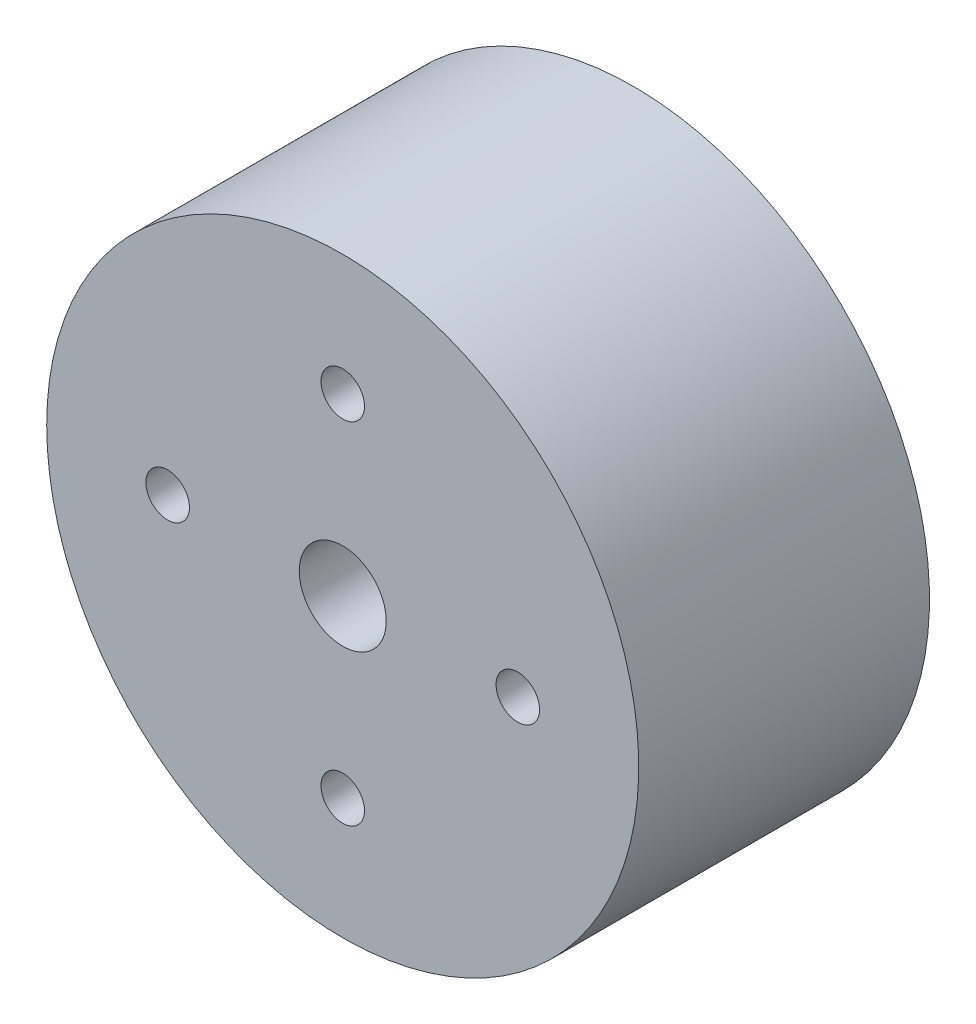
SolidWorks part; units mm, degrees
ref_plane "前视基准面" through (0, 0, 0) normal (0, 0, 1) x (1, 0, 0)
ref_plane "上视基准面" through (0, 0, 0) normal (0, 1, 0) x (1, 0, 0)
ref_plane "右视基准面" through (0, 0, 0) normal (1, 0, 0) x (0, 0, -1)
sketch "草图1" plane through (0, 0, 0) normal (0, 0, 1) x (1, 0, 0)
  circle A0 centre (0, 0) radius 13.95
  circle A1 centre (0, 0) radius 2.05
  dimension "D1" = 4.1
  dimension "D2" = 27.9
extrude "凸台-拉伸1" add sketch "草图1" along normal blind 13.7
sketch "草图2" plane through (0, 0, 0) normal (0, 0, 1) x (1, 0, 0)
  circle A0 centre (0, 0) radius 8.25 construction
  point P3 (0, 8.25)
  point P4 (8.25, 0)
  point P5 (0, -8.25)
  point P6 (-8.25, 0)
  dimension "D1" = 16.5
hole_wizard "M2.5 螺纹孔1" positions "草图3" profile "草图4" tap size "M2.5" standard "GB" end condition through all
sketch "草图3" plane through (0, 0, 13.7) normal (0, 0, 1) x (1, 0, 0)
  point P0 (0, 8.25)
  point P3 (8.25, 0)
  point P6 (0, -8.25)
  point P9 (-8.25, 0)
sketch "草图4" plane through (0, 8.25, 13.7) normal (1, 0, 0) x (0, -1, 0)
  line L0 (0, 0) -> (0, 13.7)
  line L1 (0, 13.7) -> (1.025, 13.7)
  line L2 (1.025, 13.7) -> (1.025, 0)
  line L5 (1.025, 0) -> (0, 0)
  line L11 (0, -6.35) -> (0, 107.95) construction
  dimension "通孔螺纹孔钻头直径" = 2.05
  dimension "通孔螺纹孔钻头深度" = 13.7
cosmetic thread "孔螺蚊线1"
cosmetic thread "孔螺蚊线2"
cosmetic thread "孔螺蚊线3"
cosmetic thread "孔螺蚊线4"
